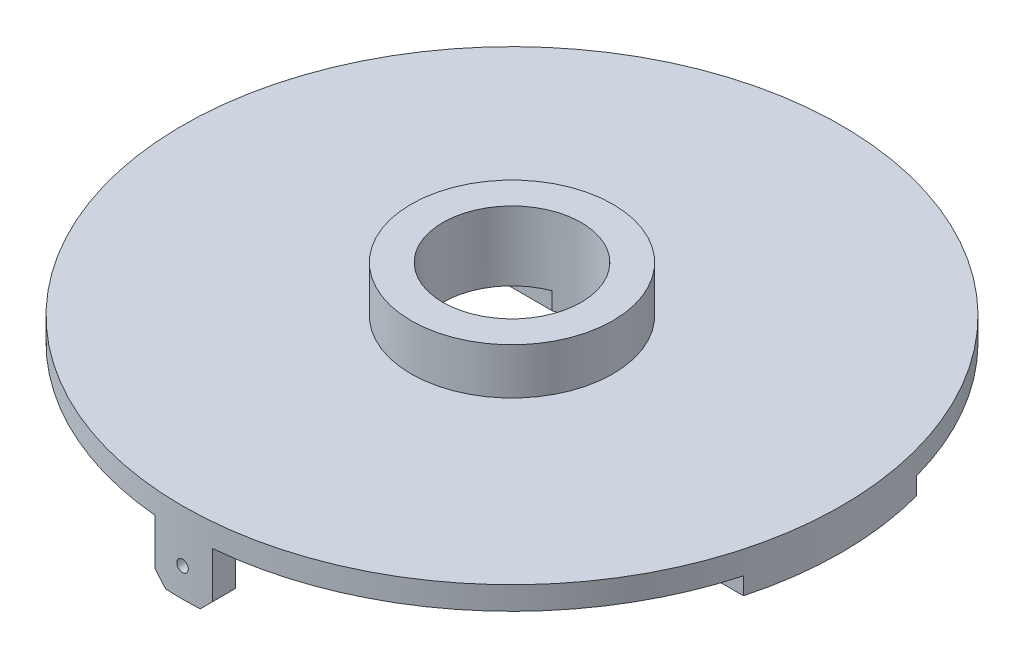
SolidWorks part; units mm, degrees
ref_plane "Front Plane" through (0, 0, 0) normal (0, 0, 1) x (1, 0, 0)
ref_plane "Top Plane" through (0, 0, 0) normal (0, 1, 0) x (1, 0, 0)
ref_plane "Right Plane" through (0, 0, 0) normal (1, 0, 0) x (0, 0, -1)
sketch "Sketch2" plane through (0, 0, 0) normal (0, 1, 0) x (1, 0, 0)
  circle A3 centre (0, 0) radius 17.5
  dimension "D1" = 35
sketch "Sketch4" plane through (0, 0, 0) normal (0, 1, 0) x (1, 0, 0)
  circle A0 centre (0, 0) radius 65
extrude "Boss-Extrude3" add sketch "Sketch2" along normal blind 8 separate body
sketch "Sketch9" plane through (0, 0, 0) normal (0, 1, 0) x (1, 0, 0)
  circle A0 centre (0, 0) radius 65
sketch "Sketch10" plane through (0, 0, 0) normal (0, 1, 0) x (1, 0, 0)
  circle A0 centre (0, 0) radius 12
extrude "Cut-Extrude3" cut sketch "Sketch10" along normal blind 8 and the other way blind 10
sketch "Sketch11" plane through (0, 0, 0) normal (0, 1, 0) x (1, 0, 0)
  line L18 (-37.5, 15) -> (17, 15)
  line L19 (-37.5, 15) -> (-37.5, -15)
  line L20 (17, 15) -> (17, -15)
  line L21 (-37.5, -15) -> (17, -15)
extrude "Boss-Extrude7" add sketch "Sketch11" against normal blind 7
sketch "Sketch12" plane through (0, 0, 0) normal (0, 1, 0) x (1, 0, 0)
  line L5 (9.4388, -10.7765) -> (-30.0612, -10.7765)
  line L6 (9.4388, -10.7765) -> (9.4388, 11.2235)
  line L7 (-30.0612, -10.7765) -> (-30.0612, 11.2235)
  line L8 (9.4388, 11.2235) -> (-30.0612, 11.2235)
extrude "Cut-Extrude4" cut sketch "Sketch12" against normal through all contours L5 L6 L8 L7
sketch "Sketch16" plane through (0, 0, 0) normal (0, 1, 0) x (1, 0, 0)
  circle A0 centre (0, 0) radius 12
sketch "Sketch18" plane through (0, 0, 0) normal (0, 1, 0) x (1, 0, 0)
  circle A0 centre (0, 0) radius 65
extrude "Cut-Extrude6" cut sketch "Sketch18" against normal blind 4
sketch "Sketch21" plane through (17, 0, 0) normal (1, 0, 0) x (0, 0, -1)
  line L6 (-15, -4) -> (15, -4)
  line L7 (-15, -4) -> (-15, -7)
  line L8 (-15, -7) -> (15, -7)
  line L9 (15, -4) -> (15, -7)
sketch "Sketch24" plane through (0, -7, 0) normal (0, -1, 0) x (1, 0, 0)
  line L0 (-37.5, -15) -> (17, -15) construction
  line L3 (-10.25, -15) -> (-10.25, 15) construction
  line L5 (-37.5, 15) -> (17, 15) construction
  circle A2 centre (-33.8112, 4.2765) radius 1
  circle A3 centre (-33.8112, -5.7235) radius 1
  circle A5 centre (13.3112, -5.7235) radius 1
  circle A6 centre (13.3112, 4.2765) radius 1
sketch "Sketch25" plane through (0, -7, 0) normal (0, -1, 0) x (1, 0, 0)
extrude "Cut-Extrude7" cut sketch "Sketch24" against normal blind 4
sketch "Sketch30" plane through (17, 0, 0) normal (1, 0, 0) x (0, 0, -1)
sketch "Sketch31" plane through (-37.5, 0, 0) normal (-1, 0, 0) x (0, 0, 1)
  line L1 (-15, -7) -> (15, -7)
  line L2 (-15, -7) -> (-15, -4)
  line L3 (-15, -4) -> (15, -4)
  line L4 (15, -7) -> (15, -4)
sketch "Sketch33" plane through (0, 0, 0) normal (0, 1, 0) x (1, 0, 0)
  circle A0 centre (0, 0) radius 57.15
extrude "Boss-Extrude8" add sketch "Sketch33" against normal blind 4
sketch "Sketch34" plane through (0, 0, 0) normal (0, 1, 0) x (1, 0, 0)
  circle A0 centre (0, 0) radius 12
extrude "Cut-Extrude8" cut sketch "Sketch34" against normal blind 7
sketch "Sketch37" plane through (0, -4, 0) normal (0, -1, 0) x (1, 0, 0)
  line L11 (-5, 52.9143) -> (-5, 56.9309)
  line L12 (5, 52.9143) -> (5, 56.9309)
  line L13 (-5, 52.9143) -> (-5, 56.9309)
  line L16 (-5, -52.9143) -> (-5, -56.9309)
  line L17 (5, -52.9143) -> (5, -56.9309)
  line L18 (5, 52.9143) -> (5, 56.9309)
  arc A16 (-5, -56.9309) -> (5, -56.9309) centre (0, 0) ccw
  arc A17 (-5, -52.9143) -> (5, -52.9143) centre (0, 0) ccw
  arc A18 (5, 56.9309) -> (-5, 56.9309) centre (0, 0) ccw
  arc A19 (5, 52.9143) -> (-5, 52.9143) centre (0, 0) ccw
  arc A20 (5, 56.9309) -> (-5, 56.9309) centre (0, 0) ccw
  arc A21 (5, 52.9143) -> (-5, 52.9143) centre (0, 0) ccw
  point P8 (0, 0)
  point P11 (0, 0)
  point P12 (-0.113, 3.9409)
  point P19 (0, 0)
  point P23 (0, 0)
  circle M9 centre (0, 0) radius 57.15
  dimension "D1" = 2
  dimension "D2" = 2
extrude "Boss-Extrude13" add sketch "Sketch37" along normal blind 10 contours A17 L16 L17 M9 | A19 L12 L11 M9
sketch3d "3DSketch10"
  line L0 (-5, -4, -56.9309) -> (5, -4, -56.9309)
  line L1 (0, -4, -56.9309) -> (0, -14, -57.15)
  arc A0 (-5, -14, -56.9309) -> (5, -14, -56.9309) centre (0, -14, 0) ccw construction
  point P9 (0, -71.15, 0)
hole_wizard "Ø1.0mm Dowel Hole1" positions "3DSketch12" profile "Sketch84" hole size "Ø1.0" standard "ANSI Metric" end condition through all
sketch3d "3DSketch12"
  point P0 (0, -9, -57.15)
  point P2 (0, -9, -57.15)
  point P4 (0, -9, -57.15)
  point P6 (0, -9, -57.15)
  point P8 (0, -9, -57.15)
  point P10 (0, -9, -57.15)
  point P12 (0, -9, -57.15)
  point P14 (0, -9, -57.15)
  point P16 (0, -9, -57.15)
  point P18 (0, -9, -57.15)
  point P20 (0, -9, -57.15)
  point P22 (0, -9, -57.15)
  point P24 (0, -9, -57.15)
  point P26 (0, -9, -57.15)
  point P28 (0, -9, -57.15)
  point P30 (0, -9, -57.15)
sketch "Sketch84" plane through (0, -9, -57.15) normal (1, 0, 0) x (0, 1, 0)
  line L0 (0, 0) -> (0, 114.3)
  line L1 (0, 114.3) -> (1, 114.3)
  line L2 (1, 114.3) -> (1, 0)
  line L5 (1, 0) -> (0, 0)
  line L11 (0, -6.35) -> (0, 107.95) construction
  dimension "Thru Hole Dia." = 2
  dimension "Thru Hole Depth" = 114.3
sketch "Sketch86" plane through (0, -4, 0) normal (0, -1, 0) x (-1, 0, 0)
  line L0 (-51.1194, -15) -> (-55.1464, -15)
  line L1 (-51.1194, 15) -> (-55.1464, 15)
  line L2 (51.1194, -15) -> (55.1464, -15)
  line L3 (51.1194, 15) -> (55.1464, 15)
  arc A0 (-55.1464, 15) -> (-55.1464, -15) centre (0, 0) ccw
  arc A1 (-51.1194, 15) -> (-51.1194, -15) centre (0, 0) ccw
  arc A2 (51.1194, -15) -> (51.1194, 15) centre (0, 0) ccw
  arc A3 (55.1464, -15) -> (55.1464, 15) centre (0, 0) ccw
extrude "Boss-Extrude14" add sketch "Sketch86" along normal blind 3
extrude "Boss-Extrude15" add sketch "Sketch21" along normal up to next
extrude "Boss-Extrude16" add sketch "Sketch31" along normal up to next contours L3 L4 L1 L2
chamfer "Chamfer1" distance 2 angle 45 4 edges at (-5, -14, 54.9226) (5, -14, 54.9226) (-5, -14, -54.9226) (5, -14, -54.9226)
